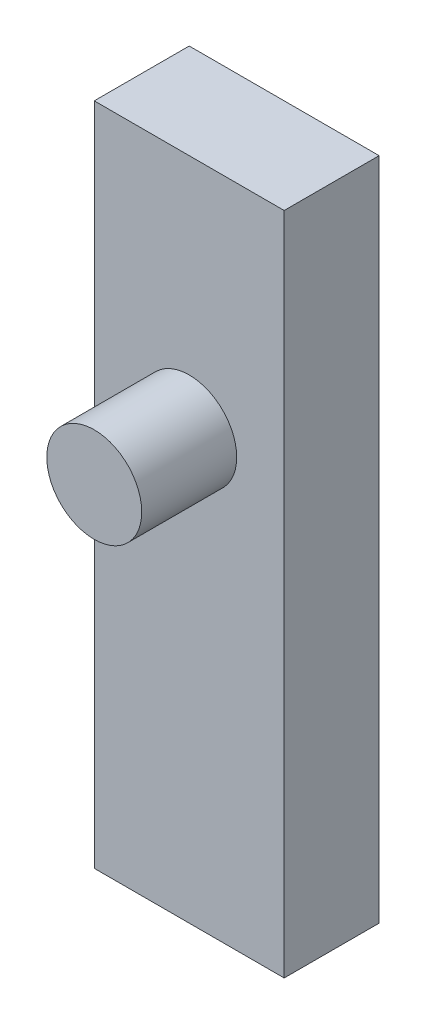
SolidWorks part; units mm, degrees
material "普通碳钢"
ref_plane "前视基准面" through (0, 0, 0) normal (0, 0, 1) x (1, 0, 0)
ref_plane "上视基准面" through (0, 0, 0) normal (0, 1, 0) x (1, 0, 0)
ref_plane "右视基准面" through (0, 0, 0) normal (1, 0, 0) x (0, 0, -1)
sketch "草图1" plane through (0, 0, 0) normal (0, 0, 1) x (1, 0, 0)
  line L1 (0, 0) -> (20, 0)
  line L2 (0, 0) -> (0, -70)
  line L3 (0, -70) -> (20, -70)
  line L4 (20, 0) -> (20, -70)
  dimension "D1" = 20
  dimension "D2" = 70
extrude "凸台-拉伸1" add sketch "草图1" along normal blind 10
sketch "草图2" plane through (0, 0, 10) normal (0, 0, 1) x (1, 0, 0)
  circle A0 centre (10, -25) radius 5
  dimension "D1" = 10
extrude "凸台-拉伸2" add sketch "草图2" along normal blind 10
